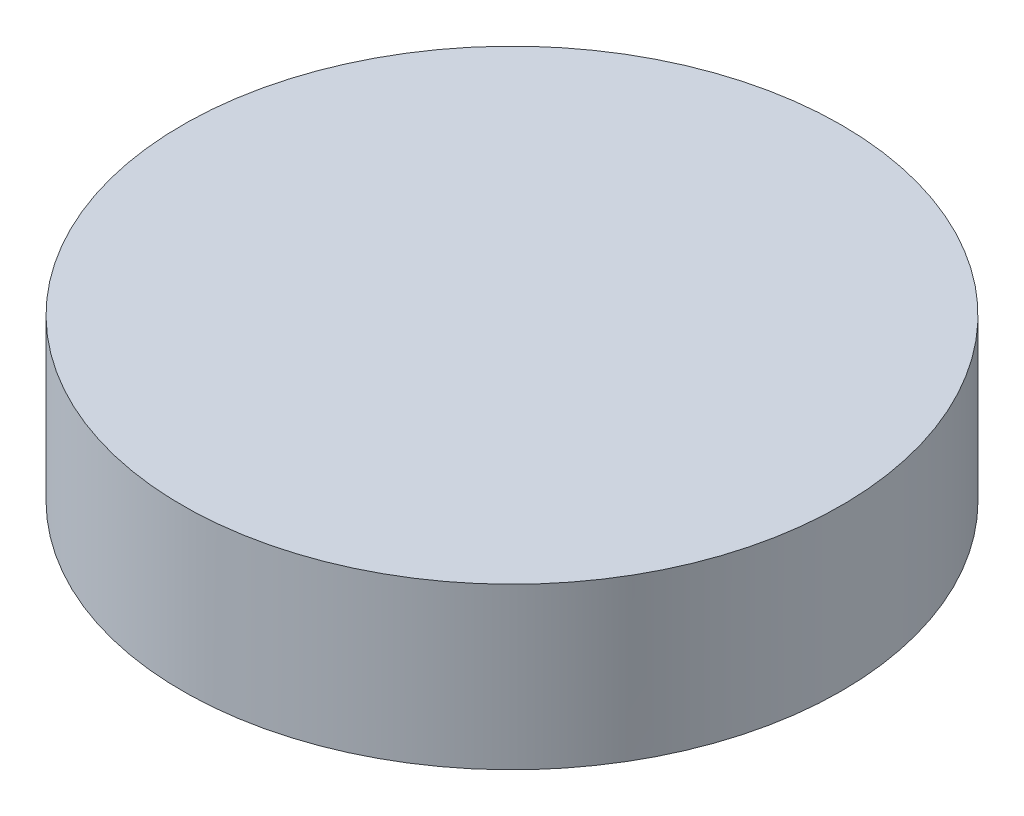
SolidWorks part; units mm, degrees
ref_plane "前视基准面" through (0, 0, 0) normal (0, 0, 1) x (1, 0, 0)
ref_plane "上视基准面" through (0, 0, 0) normal (0, 1, 0) x (1, 0, 0)
ref_plane "右视基准面" through (0, 0, 0) normal (1, 0, 0) x (0, 0, -1)
curve "曲线1"
sketch "草图4" plane through (0, 0, 0) normal (0, 0, 1) x (1, 0, 0)
  line L0 (0, 0) -> (0, 24.0748) construction
  line L1 (0, 20) -> (0, 21.832)
  line L2 (0, 21.832) -> (44.7686, 21.832)
  line L3 (44.7686, 21.832) -> (44.7686, 0)
  spline S0 degree 3 number of poles 1751 (0, 20) -> (44.7686, 0) construction
  spline S1 degree 3 number of poles 1751 (0, 20) -> (44.7686, 0)
  point P7 (0, 0)
  point P8 (44.7686, 27.6934)
  point P9 (44.7686, 27.227)
revolve "旋转1" add sketch "草图4" angle 360 about L0
